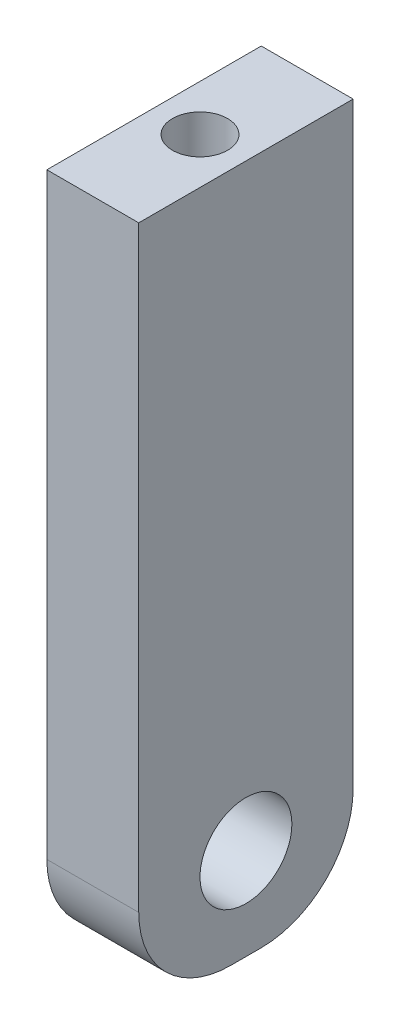
SolidWorks part; units mm, degrees
ref_plane "前视基准面" through (0, 0, 0) normal (0, 0, 1) x (1, 0, 0)
ref_plane "上视基准面" through (0, 0, 0) normal (0, 1, 0) x (1, 0, 0)
ref_plane "右视基准面" through (0, 0, 0) normal (1, 0, 0) x (0, 0, -1)
sketch "草图1" plane through (0, 0, 0) normal (0, 0, 1) x (1, 0, 0)
  line L6 (0, 0.5463) -> (0, -21.9537)
  line L7 (0, -21.9537) -> (3, -21.9537)
  line L8 (3, -21.9537) -> (3, 0.5463)
  line L9 (3, 0.5463) -> (0, 0.5463)
  dimension "D2" = 3
  dimension "24" = 22.5
extrude "凸台-拉伸1" add sketch "草图1" along normal blind 7
sketch "草图3" plane through (0, 0.5463, 0) normal (0, 1, 0) x (1, 0, 0)
  line L0 (0, -7) -> (0, 0) construction
  line L1 (3, 0) -> (0, 0) construction
  circle A0 centre (1.5, -3.5) radius 0.9
  point P6 (0, -3.5)
  point P7 (1.5, 0)
  dimension "D1" = 1.8
sketch "草图4" plane through (3, 0, 0) normal (1, 0, 0) x (0, 0, -1)
  line L0 (-7, -21.9537) -> (0, -21.9537) construction
  line L1 (-7, -21.9537) -> (-7, 0.5463) construction
  circle A0 centre (-3.5, -18.9537) radius 1.5
  dimension "D1" = 3
  dimension "D2" = 3
  dimension "D3" = 3.5
extrude "切除-拉伸2" cut sketch "草图4" against normal through all
fillet "圆角1" radius 3 2 edges at (1.5, -21.9537, 7) (1.5, -21.9537, 0)
extrude "切除-拉伸4" cut sketch "草图3" against normal blind 7
